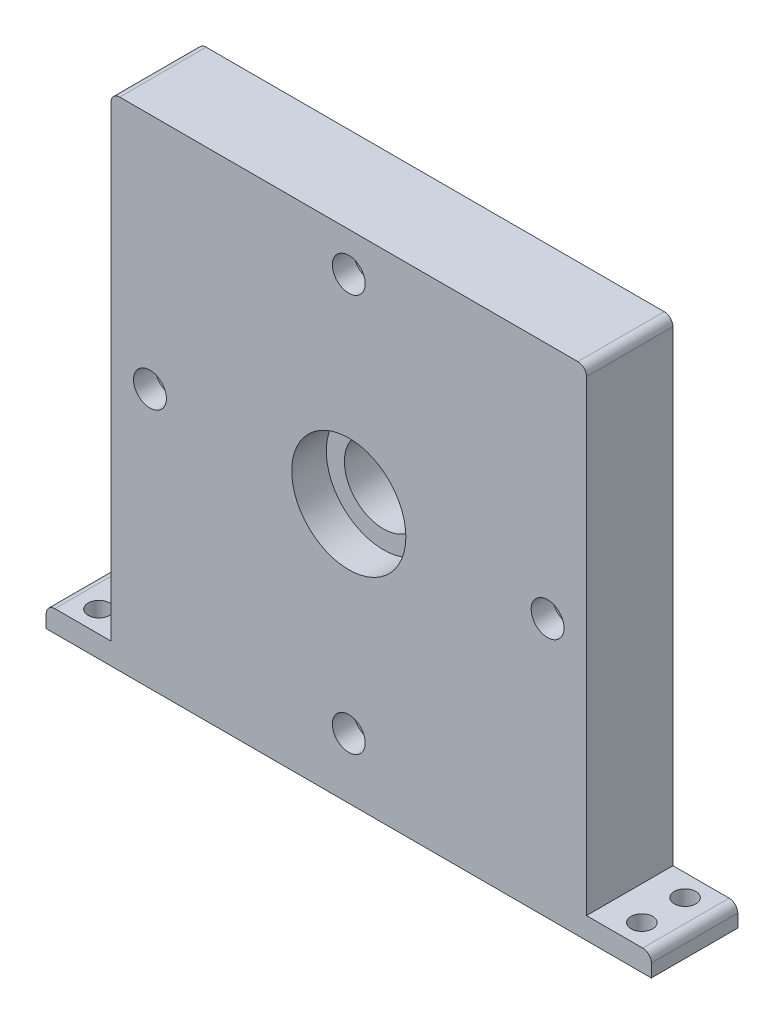
SolidWorks part; units mm, degrees
ref_plane "Front Plane" through (0, 0, 0) normal (0, 0, 1) x (1, 0, 0)
ref_plane "Top Plane" through (0, 0, 0) normal (0, 1, 0) x (1, 0, 0)
ref_plane "Right Plane" through (0, 0, 0) normal (1, 0, 0) x (0, 0, -1)
sketch "Sketch1" plane through (0, 0, 0) normal (0, 1, 0) x (1, 0, 0)
  line L1 (0, 0) -> (139.7, 0)
  line L2 (0, 0) -> (0, 12.7)
  line L3 (0, 12.7) -> (139.7, 12.7)
  line L4 (139.7, 0) -> (139.7, 12.7)
  dimension "D1" = 12.7
  dimension "D2" = 139.7
extrude "Boss-Extrude1" add sketch "Sketch1" along normal blind 146.05
sketch "Sketch2" plane through (0, 0, 0) normal (-1, 0, 0) x (0, 0, 1)
  line L0 (-12.7, 146.05) -> (-12.7, 0) construction
  line L1 (0, 0) -> (-12.7, 0)
  line L2 (0, 0) -> (0, 6.35)
  line L3 (0, 6.35) -> (-12.7, 6.35)
  line L4 (-12.7, 0) -> (-12.7, 6.35)
  dimension "D1" = 6.35
extrude "Boss-Extrude2" add sketch "Sketch2" along normal blind 19.05
ref_plane "Plane1" through (69.85, 0, 0) normal (-1, 0, 0) x (0, 0, 1)
mirror "Mirror1" about plane through (69.85, 0, 0) normal (-1, 0, 0) of "Boss-Extrude2"
sketch "Sketch3" plane through (0, 0, 0) normal (0, 0, 1) x (1, 0, 0)
  line L0 (69.85, 146.05) -> (69.85, 0) construction
  line L1 (0, 146.05) -> (139.7, 146.05) construction
  line L2 (-19.05, 0) -> (158.75, 0) construction
  circle A0 centre (69.85, 76.2) radius 16.764
  dimension "D2" = 33.528
  dimension "D1" = 76.2
sketch "Sketch6" plane through (0, 6.35, 0) normal (0, 1, 0) x (1, 0, 0)
  line L0 (0, 0) -> (0, 12.7) construction
  line L3 (0, 6.35) -> (-19.05, 6.35) construction
  line L4 (-19.05, 0) -> (-19.05, 12.7) construction
  circle A0 centre (-9.906, 6.35) radius 3.175
  dimension "D1" = 6.35
  dimension "D2" = 9.906
extrude "Cut-Extrude4" cut sketch "Sketch6" against normal up to next
mirror "Mirror2" about plane through (69.85, 0, 0) normal (-1, 0, 0) of "Cut-Extrude4"
fillet "Fillet1" radius 2.54 4 edges at (158.75, 6.35, -6.35) (-19.05, 6.35, -6.35) (139.7, 146.05, -6.35) (0, 146.05, -6.35)
extrude "Cut-Extrude5" cut sketch "Sketch3" against normal offset from surface (10.16 mm away) 2.54 contours A0 up to face at (69.85, 51.187, -12.7)
sketch "Sketch7" plane through (0, 0, -10.16) normal (0, 0, 1) x (1, 0, 0)
  circle A0 centre (69.85, 76.2) radius 11.4554
  circle A1 centre (69.85, 76.2) radius 16.764 construction
  dimension "D1" = 22.9108
extrude "Cut-Extrude6" cut sketch "Sketch7" against normal through all contours A0
sketch "Sketch8" plane through (0, 0, -12.7) normal (0, 0, -1) x (-1, 0, 0)
  line L7 (-137.16, 146.05) -> (-2.54, 146.05)
  line L8 (-139.7, 143.51) -> (-139.7, 6.35)
  line L10 (0, 6.35) -> (0, 143.51)
  line L11 (-139.7, 6.35) -> (-156.21, 6.35)
  line L12 (-158.75, 3.81) -> (-158.75, 0)
  line L13 (-158.75, 0) -> (19.05, 0)
  line L14 (19.05, 0) -> (19.05, 3.81)
  line L15 (16.51, 6.35) -> (0, 6.35)
  arc A2 (-2.54, 146.05) -> (0, 143.51) centre (-2.54, 143.51) cw
  arc A3 (-139.7, 143.51) -> (-137.16, 146.05) centre (-137.16, 143.51) cw
  arc A4 (16.51, 6.35) -> (19.05, 3.81) centre (16.51, 3.81) cw
  arc A5 (-158.75, 3.81) -> (-156.21, 6.35) centre (-156.21, 3.81) cw
  circle A6 centre (-69.85, 76.2) radius 11.4554 construction
  point P9 (-69.85, 76.2)
extrude "Boss-Extrude3" add sketch "Sketch8" along normal blind 12.7
ref_plane "Plane2" through (0, 0, -12.7) normal (0, 0, -1) x (-1, 0, 0)
ref_plane "Plane3" through (0, 0, -12.7) normal (0, 0, 1) x (1, 0, 0)
mirror "Mirror3" about plane through (0, 0, -12.7) normal (0, 0, -1) of "Mirror2", "Cut-Extrude4"
sketch "Sketch10" plane through (0, 0, 0) normal (0, 0, 1) x (1, 0, 0)
  line L0 (69.85, 76.2) -> (69.85, 134.62) construction
  line L1 (69.85, 76.2) -> (11.43, 76.2) construction
  circle A0 centre (69.85, 76.2) radius 58.42 construction
  circle A1 centre (11.43, 76.2) radius 3.3782
  circle A2 centre (69.85, 134.62) radius 3.3782
  circle A3 centre (128.27, 76.2) radius 3.3782
  circle A4 centre (69.85, 17.78) radius 3.3782
  point P15 (69.85, 76.2)
  dimension "D1" = 116.84
  dimension "D3" = 6.7564
  dimension "D2" = 90
  dimension "D4" = 4
extrude "Cut-Extrude8" cut sketch "Sketch10" against normal through all
sketch "Sketch11" plane through (0, 0, 0) normal (0, 0, 1) x (1, 0, 0)
  circle A0 centre (11.43, 76.2) radius 4.826
  circle A1 centre (69.85, 134.62) radius 4.826
  circle A2 centre (128.27, 76.2) radius 4.826
  circle A3 centre (69.85, 17.78) radius 4.826
  circle A4 centre (69.85, 76.2) radius 16.764 construction
  point P12 (69.85, 76.2)
  dimension "D1" = 9.652
  dimension "D2" = 4
extrude "Cut-Extrude9" cut sketch "Sketch11" against normal blind 6.35
sketch "Sketch12" plane through (0, 0, -12.7) normal (0, 0, 1) x (1, 0, 0)
  circle A0 centre (69.85, 76.2) radius 11.4554
  circle A1 centre (69.85, 76.2) radius 11.4554 construction
extrude "Cut-Extrude10" cut sketch "Sketch12" against normal through all
